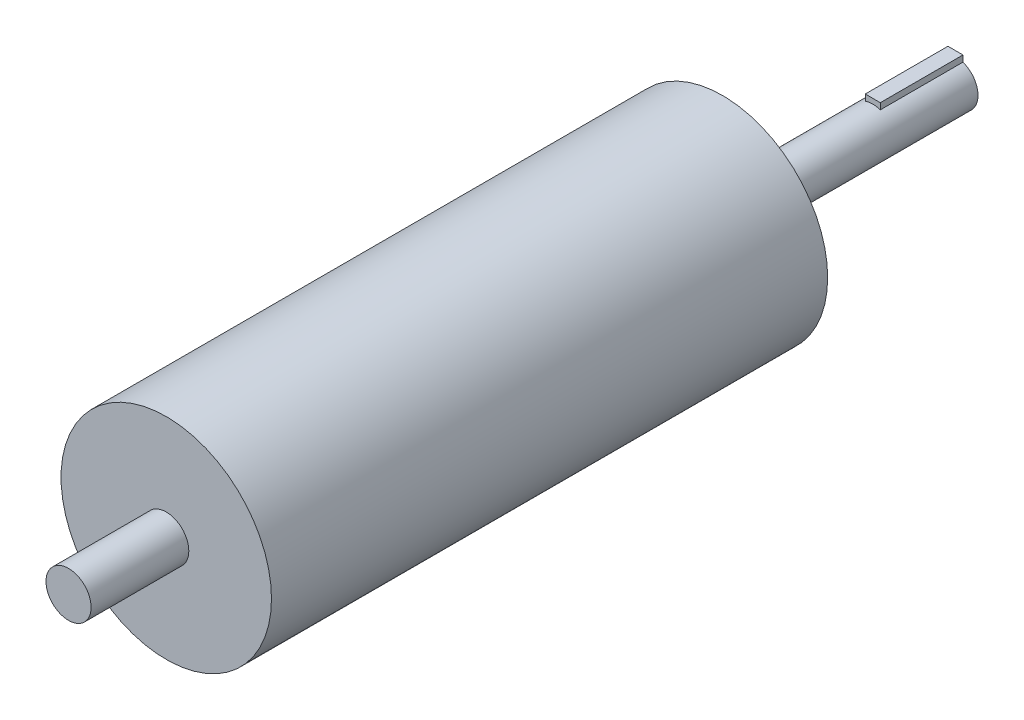
SolidWorks part; units mm, degrees
material "1023 Carbon Steel Sheet (SS)"
ref_plane "Front Plane" through (0, 0, 0) normal (0, 0, 1) x (1, 0, 0)
ref_plane "Top Plane" through (0, 0, 0) normal (0, 1, 0) x (1, 0, 0)
ref_plane "Right Plane" through (0, 0, 0) normal (1, 0, 0) x (0, 0, -1)
sketch "Sketch1" plane through (0, 0, 0) normal (0, 0, 1) x (1, 0, 0)
  circle A0 centre (0, 0) radius 70
  dimension "D1" = 140
extrude "Boss-Extrude1" add sketch "Sketch1" along normal blind 370
sketch "Sketch4" plane through (0, 0, 370) normal (0, 0, 1) x (1, 0, 0)
  circle A0 centre (0, 0) radius 10
extrude "Boss-Extrude2" add sketch "Sketch4" along normal blind 80
sketch "Sketch5" plane through (0, 0, 0) normal (0, 0, -1) x (-1, 0, 0)
  circle A0 centre (0, 0) radius 10
extrude "Boss-Extrude3" add sketch "Sketch5" along normal blind 100
sketch "Sketch6" plane through (0, 0, 450) normal (0, 0, 1) x (1, 0, 0)
  circle A0 centre (0, 0) radius 10
extrude "Cut-Extrude1" cut sketch "Sketch6" against normal blind 15
sketch "Sketch7" plane through (0, 0, -100) normal (0, 0, -1) x (-1, 0, 0)
  line L0 (0, 10) -> (-5, 10) construction
  line L1 (0, 10) -> (5, 10) construction
  line L2 (5, 8.6603) -> (5, 12.8203)
  line L3 (5, 12.8203) -> (-5, 12.8203)
  line L4 (-5, 12.8203) -> (-5, 8.6603)
  circle A0 centre (0, 0) radius 10 construction
  circle A1 centre (0, 0) radius 10 construction
  arc A2 (5, 8.6603) -> (-5, 8.6603) centre (0, 0) ccw
extrude "Boss-Extrude4" add sketch "Sketch7" against normal blind 25
sketch "Sketch8" plane through (0, 0, -100) normal (0, 0, -1) x (-1, 0, 0)
  circle A0 centre (0, 0) radius 15
extrude "Boss-Extrude5" add sketch "Sketch8" against normal blind 535
sketch "Sketch9" plane through (0, 0, -100) normal (0, 0, -1) x (-1, 0, 0)
  line L0 (0, 15) -> (5, 15) construction
  line L1 (0, 15) -> (-5, 15) construction
  line L2 (-5, 14.1421) -> (-5, 18.3021)
  line L3 (-5, 18.3021) -> (5, 18.3021)
  line L4 (5, 18.3021) -> (5, 14.1421)
  circle A0 centre (0, 0) radius 15 construction
  circle A1 centre (0, 0) radius 15 construction
  arc A2 (5, 14.1421) -> (-5, 14.1421) centre (0, 0) ccw
extrude "Boss-Extrude7" add sketch "Sketch9" along normal blind 55 separate body
sketch "Sketch10" plane through (0, 0, -100) normal (0, 0, -1) x (-1, 0, 0)
  circle A0 centre (0, 0) radius 15
extrude "Boss-Extrude8" add sketch "Sketch10" along normal blind 55
